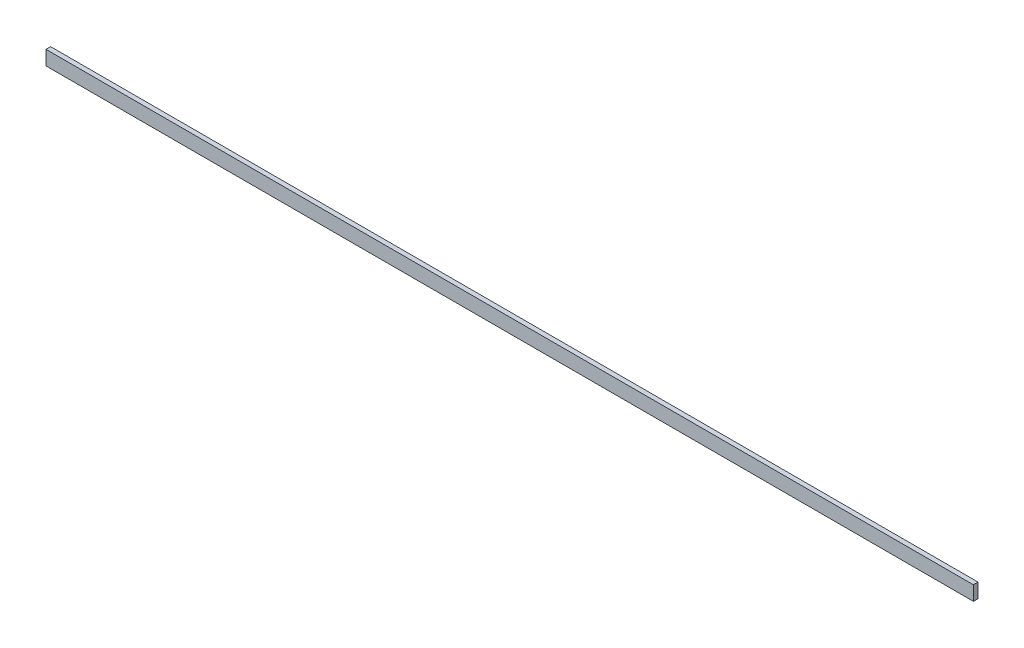
SolidWorks part; units mm, degrees
ref_plane "Plan de face" through (0, 0, 0) normal (0, 0, 1) x (1, 0, 0)
ref_plane "Plan de dessus" through (0, 0, 0) normal (0, 1, 0) x (1, 0, 0)
ref_plane "Plan de droite" through (0, 0, 0) normal (1, 0, 0) x (0, 0, -1)
sketch "Esquisse1" plane through (0, 0, 0) normal (0, 0, 1) x (1, 0, 0)
  line L1 (-10.4953, 2.0443) -> (19989.5047, 2.0443)
  line L2 (-10.4953, 2.0443) -> (-10.4953, -307.9557)
  line L3 (-10.4953, -307.9557) -> (19989.5047, -307.9557)
  line L4 (19989.5047, 2.0443) -> (19989.5047, -307.9557)
  dimension "D1" = 20000
  dimension "D2" = 310
extrude "Boss.-Extru.1" add sketch "Esquisse1" along normal blind 100
